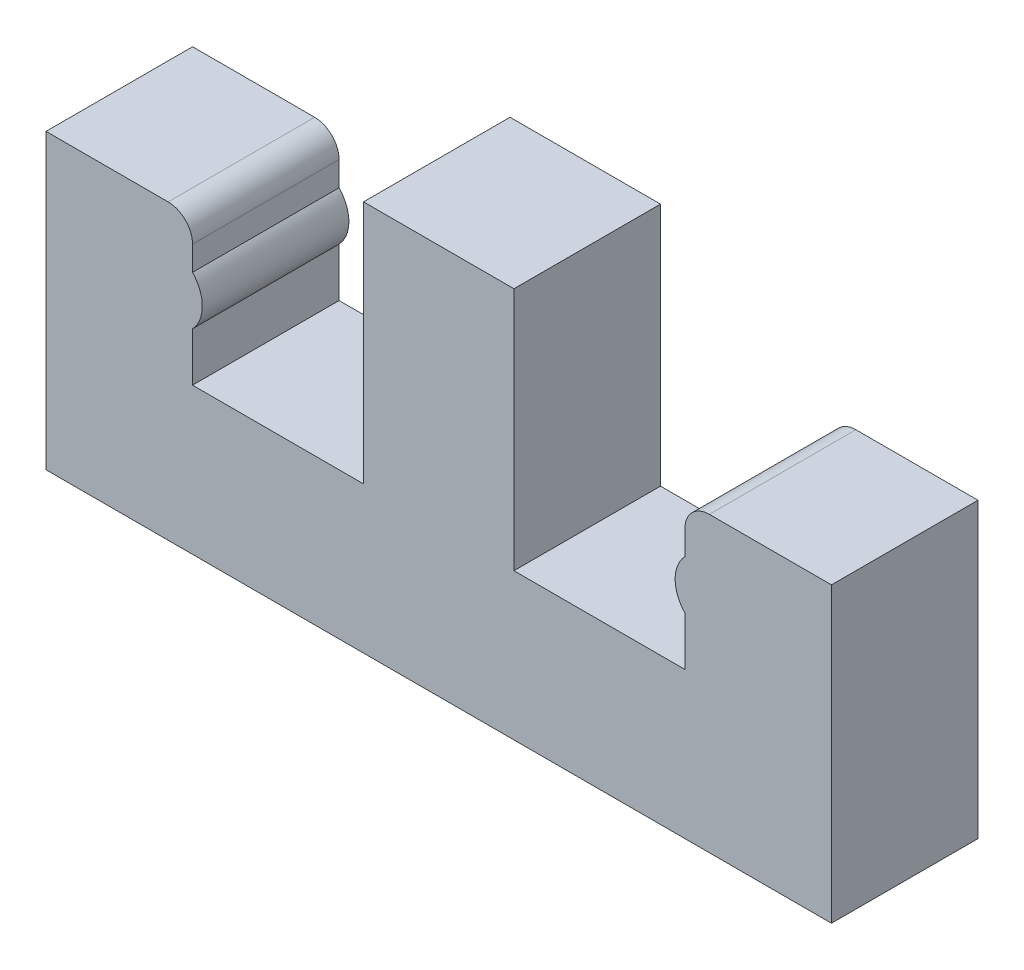
SolidWorks part; units mm, degrees
ref_plane "Front Plane" through (0, 0, 0) normal (0, 0, 1) x (1, 0, 0)
ref_plane "Top Plane" through (0, 0, 0) normal (0, 1, 0) x (1, 0, 0)
ref_plane "Right Plane" through (0, 0, 0) normal (1, 0, 0) x (0, 0, -1)
sketch "Sketch1" plane through (0, 0, 0) normal (0, 0, 1) x (1, 0, 0)
  line L0 (-5.3504, -2.2692) -> (10.7296, -2.2692)
  line L1 (10.7296, -2.2692) -> (10.7296, 3.7308)
  line L2 (10.7296, 3.7308) -> (7.7296, 3.7308)
  line L3 (7.7296, 2.7308) -> (7.7296, 3.7308)
  line L4 (7.7296, 0.7308) -> (4.2296, 0.7308)
  line L5 (4.2296, 0.7308) -> (4.2296, 5.7308)
  line L6 (4.2296, 5.7308) -> (1.1496, 5.7308)
  line L7 (1.1496, 5.7308) -> (1.1496, 0.7308)
  line L8 (1.1496, 0.7308) -> (-2.3504, 0.7308)
  line L9 (-2.3504, 1.7308) -> (-2.3504, 0.7308)
  line L10 (-5.3504, -2.2692) -> (-5.3504, 3.7308)
  line L11 (-5.3504, 3.7308) -> (-2.3504, 3.7308)
  line L12 (7.7296, 1.7308) -> (7.7296, 0.7308)
  line L16 (2.6896, 5.7308) -> (2.6896, -0.2829) construction
  line L17 (-2.3504, 2.7308) -> (-2.3504, 3.7308)
  arc A0 (-2.3504, 2.7308) -> (-2.3504, 1.7308) centre (-2.8754, 2.2308) cw
  arc A1 (7.7296, 2.7308) -> (7.7296, 1.7308) centre (8.2546, 2.2308) ccw
  dimension "D2" = 6
  dimension "D4" = 3
  dimension "D5" = 3.5
  dimension "D6" = 5
  dimension "D7" = 3.08
  dimension "D8" = 5
  dimension "D10" = 3
  dimension "D11" = 3
  dimension "D12" = 6
  dimension "D13" = 3
extrude "Boss-Extrude1" add sketch "Sketch1" along normal blind 3
fillet "Fillet1" radius 0.5 2 edges at (-2.3504, 3.7308, 1.5) (7.7296, 3.7308, 1.5)
